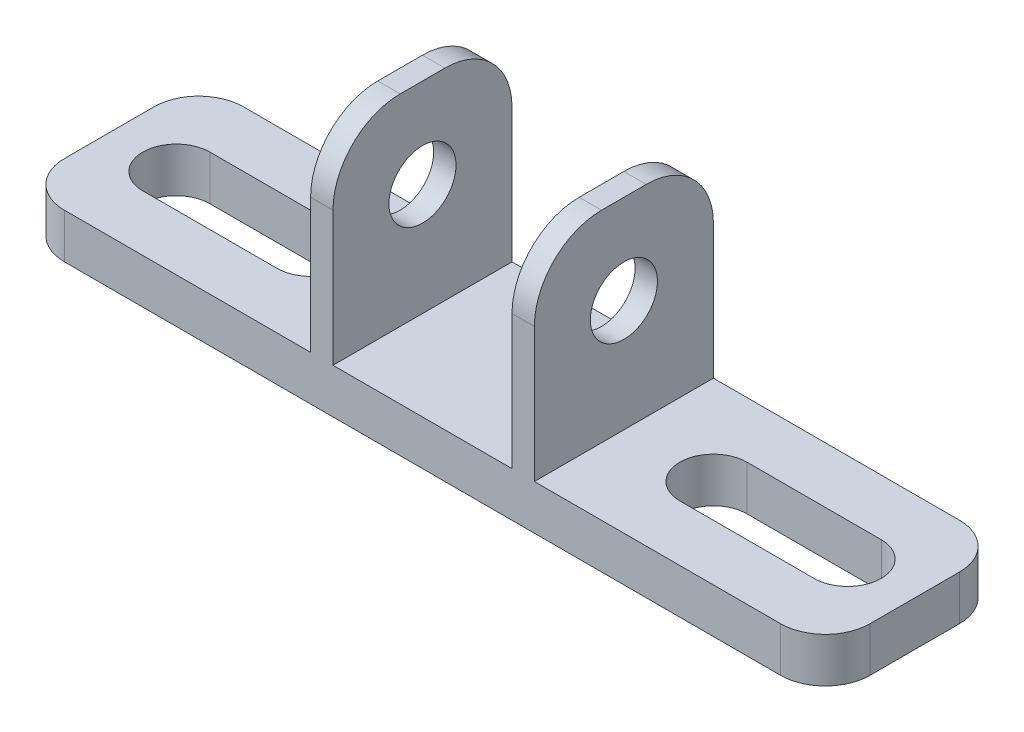
SolidWorks part; units mm, degrees
material "尼龙 101"
ref_plane "前视基准面" through (0, 0, 0) normal (0, 0, 1) x (1, 0, 0)
ref_plane "上视基准面" through (0, 0, 0) normal (0, 1, 0) x (1, 0, 0)
ref_plane "右视基准面" through (0, 0, 0) normal (1, 0, 0) x (0, 0, -1)
other "Configuration Table"
sketch "草图1" plane through (0, 0, 0) normal (0, 1, 0) x (1, 0, 0)
  line L0 (-9, 0) -> (-15, 0) construction
  line L1 (-16, 4) -> (16, 4)
  line L2 (-18, 2) -> (-18, -2)
  line L3 (-16, -4) -> (16, -4)
  line L4 (18, 2) -> (18, -2)
  line L5 (-9, -1.5) -> (-15, -1.5)
  line L6 (-9, 1.5) -> (-15, 1.5)
  line L7 (9, 0) -> (15, 0) construction
  line L8 (9, 1.5) -> (15, 1.5)
  line L9 (9, -1.5) -> (15, -1.5)
  arc A0 (16, -4) -> (18, -2) centre (16, -2) ccw
  arc A1 (18, 2) -> (16, 4) centre (16, 2) ccw
  arc A2 (-16, -4) -> (-18, -2) centre (-16, -2) cw
  arc A3 (-18, 2) -> (-16, 4) centre (-16, 2) cw
  arc A4 (-9, -1.5) -> (-9, 1.5) centre (-9, 0) ccw
  arc A5 (-15, 1.5) -> (-15, -1.5) centre (-15, 0) ccw
  arc A6 (9, 1.5) -> (9, -1.5) centre (9, 0) ccw
  arc A7 (15, -1.5) -> (15, 1.5) centre (15, 0) ccw
  point P6 (18, -4)
  point P11 (-18, -4)
  point P14 (-18, 4)
  point P15 (-9, 0)
  point P17 (9, 0)
  point P20 (-12, 0)
  point P27 (12, 0)
  dimension "D3" = 2
  dimension "D1" = 8
  dimension "D2" = 36
  dimension "D4" = 4
  dimension "D5" = 9
  dimension "D6" = 9
  dimension "D7" = 6
  dimension "D8" = 3
  dimension "D9" = 18
  dimension "D10" = 6
  dimension "D11" = 3
extrude "凸台-拉伸1" add sketch "草图1" along normal blind 2
sketch "草图2" plane through (0, 2, 0) normal (0, 1, 0) x (1, 0, 0)
  line L0 (4, 4) -> (4, -4)
  line L1 (16, 4) -> (-16, 4) construction
  line L2 (-16, -4) -> (16, -4) construction
  line L3 (-4, 4) -> (-4, -4)
  line L4 (5, 4) -> (5, -4)
  line L5 (-5, 4) -> (-5, -4)
  line L6 (-5, -4) -> (-4, -4)
  line L7 (-5, 4) -> (-4, 4)
  line L8 (4, 4) -> (5, 4)
  line L9 (4, -4) -> (5, -4)
  dimension "D1" = 4
  dimension "D2" = 4
  dimension "D3" = 1
  dimension "D4" = 1
extrude "凸台-拉伸2" add sketch "草图2" along normal blind 9
fillet "圆角2" radius 3 4 edges at (4.5, 11, -4) (4.5, 11, 4) (-4.5, 11, 4) (-4.5, 11, -4)
sketch "草图3" plane through (-5, 0, 0) normal (-1, 0, 0) x (0, 0, 1)
  line L0 (-1, 11) -> (1, 11) construction
  circle A0 centre (0, 7) radius 1.5
  point P0 (0, 7)
  dimension "D1" = 4
extrude "切除-拉伸1" cut sketch "草图3" against normal blind 20
